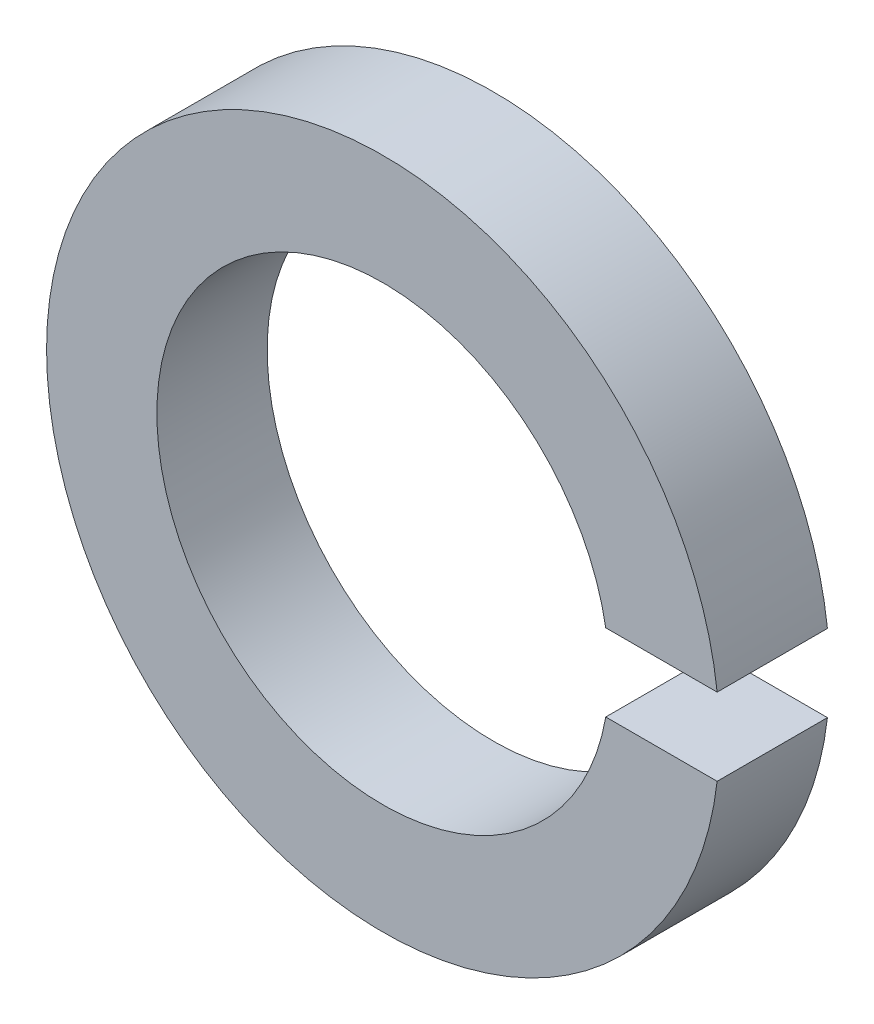
SolidWorks part; units mm, degrees
ref_plane "Спереди" through (0, 0, 0) normal (0, 0, 1) x (1, 0, 0)
ref_plane "Сверху" through (0, 0, 0) normal (0, 1, 0) x (1, 0, 0)
ref_plane "Справа" through (0, 0, 0) normal (1, 0, 0) x (0, 0, -1)
sketch "Эскиз1" plane through (0, 0, 0) normal (0, 0, 1) x (1, 0, 0)
  circle A0 centre (0, 0) radius 6.1
  circle A1 centre (0, 0) radius 4.1
  dimension "D1" = 12.2
  dimension "D2" = 8.2
extrude "Вытянуть1" add sketch "Эскиз1" along normal blind 2
sketch "Эскиз2" plane through (0, 0, 2) normal (0, 0, 1) x (1, 0, 0)
  line L0 (0, 0) -> (0.123, 0) construction
  line L1 (6.1, 0) -> (-6.1, 0) construction
  line L3 (3.9601, 0.7) -> (6.2313, 0.7)
  line L4 (3.9601, 0.7) -> (3.9601, -0.7)
  line L5 (3.9601, -0.7) -> (6.2313, -0.7)
  line L6 (6.2313, 0.7) -> (6.2313, -0.7)
  circle A0 centre (0, 0) radius 6.1 construction
  dimension "D1" = 0.7
  dimension "D2" = 1.4
extrude "Вырез-Вытянуть1" cut sketch "Эскиз2" against normal through all
